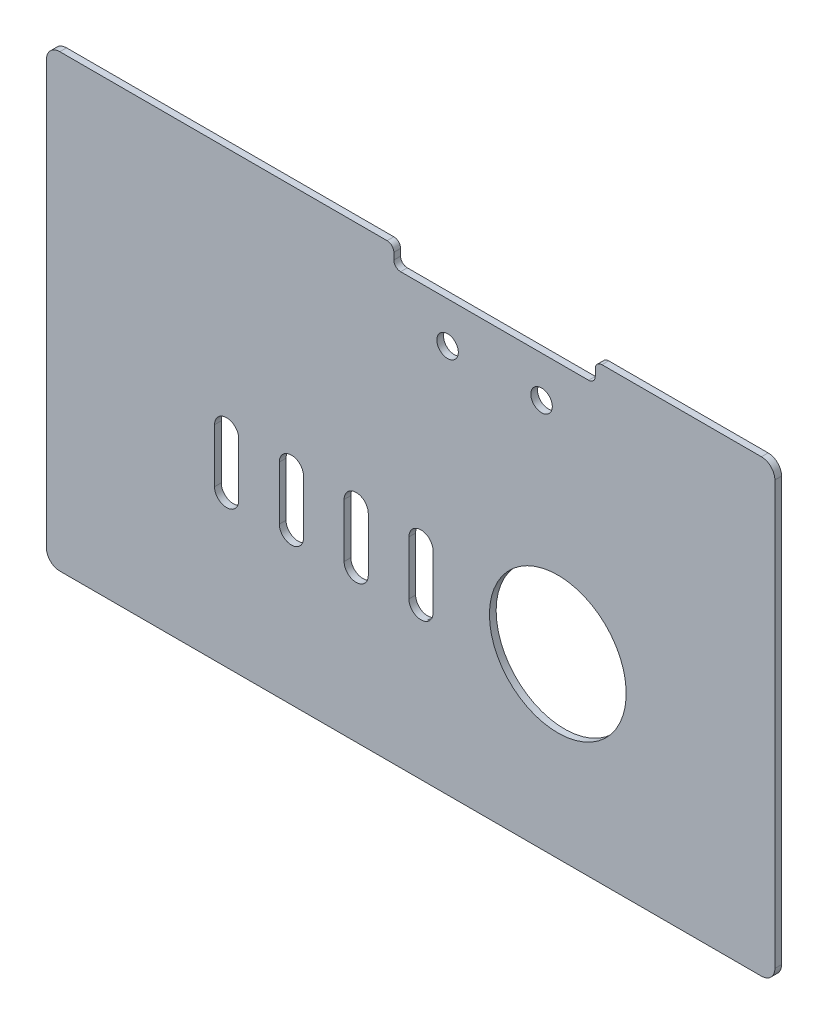
SolidWorks part; units mm, degrees
material "Thornel Mat VMA"
ref_plane "前视基准面" through (0, 0, 0) normal (0, 0, 1) x (1, 0, 0)
ref_plane "上视基准面" through (0, 0, 0) normal (0, 1, 0) x (1, 0, 0)
ref_plane "右视基准面" through (0, 0, 0) normal (1, 0, 0) x (0, 0, -1)
other "Configuration Table"
sketch "草图1" plane through (0, 0, 0) normal (0, 0, 1) x (1, 0, 0)
  line L0 (0, 0) -> (0, -50000) construction
  line L1 (-63.75, -35) -> (63.75, -35)
  line L2 (-63.75, -35) -> (-63.75, 35)
  line L3 (-63.75, 35) -> (63.75, 35)
  line L4 (63.75, -35) -> (63.75, 35)
  line L5 (-63.75, -35) -> (63.75, 35) construction
  line L6 (-63.75, 35) -> (63.75, -35) construction
  line L7 (-7, 22.9) -> (7, 22.9) construction
  circle A0 centre (-7, 22.9) radius 1.6
  circle A1 centre (7, 22.9) radius 1.6
  point P0 (0, 0)
  point P11 (0, 22.9)
  dimension "D4" = 3.2
  dimension "D1" = 70
  dimension "D2" = 127.5
  dimension "D3" = 12.1
  dimension "D5" = 14
extrude "凸台-拉伸1" add sketch "草图1" along normal blind 1
sketch "草图2" plane through (0, 0, 1) normal (0, 0, 1) x (1, 0, 0)
  line L0 (63.75, -35) -> (63.75, 35) construction
  line L1 (-63.75, 35) -> (63.75, 35)
  line L2 (-63.75, 35) -> (-63.75, 32)
  line L3 (-63.75, 32) -> (63.75, 32)
  line L4 (63.75, 35) -> (63.75, 32)
  dimension "D1" = 3
extrude "切除-拉伸1" cut sketch "草图2" against normal blind 10
sketch "草图3" plane through (0, 0, 1) normal (0, 0, 1) x (1, 0, 0)
  line L0 (-63.75, -35) -> (63.75, -35) construction
  line L1 (63.75, 32) -> (41.75, 32)
  line L2 (63.75, 32) -> (63.75, -35)
  line L3 (63.75, -35) -> (41.75, -35)
  line L4 (41.75, 32) -> (41.75, -35)
  dimension "D1" = 22
extrude "切除-拉伸2" cut sketch "草图3" against normal blind 10
sketch "草图4" plane through (0, 0, 1) normal (0, 0, 1) x (1, 0, 0)
  line L1 (-63.75, 32) -> (-66.75, 32)
  line L2 (-63.75, 32) -> (-63.75, -35)
  line L3 (-63.75, -35) -> (-66.75, -35)
  line L4 (-66.75, 32) -> (-66.75, -35)
  dimension "D1" = 3
extrude "凸台-拉伸3" add sketch "草图4" against normal blind 1
sketch "草图5" plane through (0, 0, 1) normal (0, 0, 1) x (1, 0, 0)
  line L0 (-7, 22.9) -> (7, 22.9) construction
  line L1 (0, 22.9) -> (0, 32) construction
  line L2 (-66.75, 32) -> (41.75, 32) construction
  line L4 (-15, 29) -> (15, 29)
  line L5 (-15, 29) -> (-15, 35)
  line L6 (-15, 35) -> (15, 35)
  line L7 (15, 29) -> (15, 35)
  line L8 (-15, 29) -> (15, 35) construction
  line L9 (-15, 35) -> (15, 29) construction
  dimension "D1" = 30
  dimension "D2" = 6
extrude "切除-拉伸3" cut sketch "草图5" against normal mid plane 10
fillet "圆角1" radius 1 4 edges at (15, 32, 0.5) (15, 29, 0.5) (-15, 29, 0.5) (-15, 32, 0.5)
fillet "圆角2" radius 2 4 edges at (-66.75, -35, 0.5) (41.75, -35, 0.5) (41.75, 32, 0.5) (-66.75, 32, 0.5)
sketch "草图6" plane through (0, 0, 0) normal (0, 0, -1) x (-1, 0, 0)
  line L8 (40.7094, -12.59) -> (40.7094, -4.59) construction
  line L9 (39.1094, -4.59) -> (39.1094, -12.59) construction
  line L10 (31.0594, -12.59) -> (31.0594, -4.59) construction
  line L11 (29.4594, -4.59) -> (29.4594, -12.59) construction
  line L12 (21.4094, -12.59) -> (21.4094, -4.59) construction
  line L13 (19.8094, -4.59) -> (19.8094, -12.59) construction
  line L14 (11.76, -12.59) -> (11.7602, -4.59) construction
  line L15 (10.1613, -4.59) -> (10.1609, -12.59) construction
  line L16 (66.75, 30) -> (66.75, -33) construction
  line L17 (64.75, -35) -> (-39.75, -35) construction
  line L18 (12.76, -12.5908) -> (12.7602, -4.59)
  line L19 (9.1613, -4.5892) -> (9.1609, -12.59)
  line L20 (22.4094, -12.59) -> (22.4094, -4.59)
  line L21 (18.8094, -4.59) -> (18.8094, -12.59)
  line L22 (32.0594, -12.59) -> (32.0594, -4.59)
  line L23 (28.4594, -4.59) -> (28.4594, -12.59)
  line L24 (41.7094, -12.59) -> (41.7094, -4.59)
  line L25 (38.1094, -4.59) -> (38.1094, -12.59)
  arc A7 (39.1094, -12.59) -> (40.7094, -12.59) centre (39.9094, -12.59) ccw construction
  arc A8 (40.7094, -4.59) -> (39.1094, -4.59) centre (39.9094, -4.59) ccw construction
  arc A9 (31.0594, -4.59) -> (29.4594, -4.59) centre (30.2594, -4.59) ccw construction
  arc A10 (29.4594, -12.59) -> (31.0594, -12.59) centre (30.2594, -12.59) ccw construction
  arc A11 (21.4094, -4.59) -> (19.8094, -4.59) centre (20.6094, -4.59) ccw construction
  arc A12 (19.8094, -12.59) -> (21.4094, -12.59) centre (20.6094, -12.59) ccw construction
  circle A13 centre (-9.42, -8.6) radius 10.1849
  arc A14 (22.4094, -4.59) -> (18.8094, -4.59) centre (20.6094, -4.59) ccw
  arc A15 (18.8094, -12.59) -> (22.4094, -12.59) centre (20.6094, -12.59) ccw
  arc A16 (32.0594, -4.59) -> (28.4594, -4.59) centre (30.2594, -4.59) ccw
  arc A17 (28.4594, -12.59) -> (32.0594, -12.59) centre (30.2594, -12.59) ccw
  arc A18 (38.1094, -12.59) -> (41.7094, -12.59) centre (39.9094, -12.59) ccw
  arc A19 (41.7094, -4.59) -> (38.1094, -4.59) centre (39.9094, -4.59) ccw
  spline S2 degree 3 poles (11.7602, -4.59) (11.7603, -4.381) (11.6744, -4.1731) (11.3789, -3.877) (11.171, -3.7907) (10.7524, -3.7904) (10.5443, -3.8764) (10.2479, -4.1724) (10.1615, -4.3805) (10.1613, -4.59) knots 0 0 0 0 0.25 0.25 0.5 0.5 0.75 0.75 1 1 1 1 construction
  spline S3 degree 3 poles (10.1609, -12.59) (10.1609, -12.7989) (10.2469, -13.0067) (10.5425, -13.3025) (10.7502, -13.3887) (11.1686, -13.3891) (11.3767, -13.3031) (11.6731, -13.0075) (11.7597, -12.7995) (11.76, -12.59) knots 0 0 0 0 0.25 0.25 0.5 0.5 0.75 0.75 1 1 1 1 construction
  spline S4 degree 1 poles (12.7602, -4.59) (9.1613, -4.5892) knots 0 0 1 1 construction
  spline S5 degree 1 poles (9.1609, -12.59) (12.76, -12.5908) knots 0 0 1 1 construction
  spline S6 degree 3 poles (12.7602, -4.59) (12.7603, -4.1312) (12.3716, -3.1752) (10.9623, -2.5987) (9.5519, -3.1736) (9.1617, -4.13) (9.1613, -4.5892) knots 0.000124 0.000124 0.000124 0.000124 0.250093 0.500062 0.750031 1 1 1 1
  spline S7 degree 3 poles (9.1609, -12.59) (9.1609, -13.0488) (9.5499, -14.0046) (10.9593, -14.5809) (12.3699, -14.0052) (12.7592, -13.0497) (12.76, -12.5908) knots -0.000006 -0.000006 -0.000006 -0.000006 0.250075 0.500157 0.750239 1.00032 1.00032 1.00032 1.00032
  dimension "D1" = 20.3699
  dimension "D2" = 0.8
  dimension "D3" = 26.8406
  dimension "D4" = 36.4906
  dimension "D5" = 46.1406
  dimension "D6" = 54.9898
  dimension "D7" = 54.99
  dimension "D8" = 56.5887
  dimension "D9" = 56.5891
  dimension "D10" = 76.17
  dimension "D11" = 22.41
  dimension "D12" = 1
  dimension "D13" = 26.4
  dimension "D16" = 30.41
extrude "切除-拉伸4" cut sketch "草图6" against normal mid plane 10
